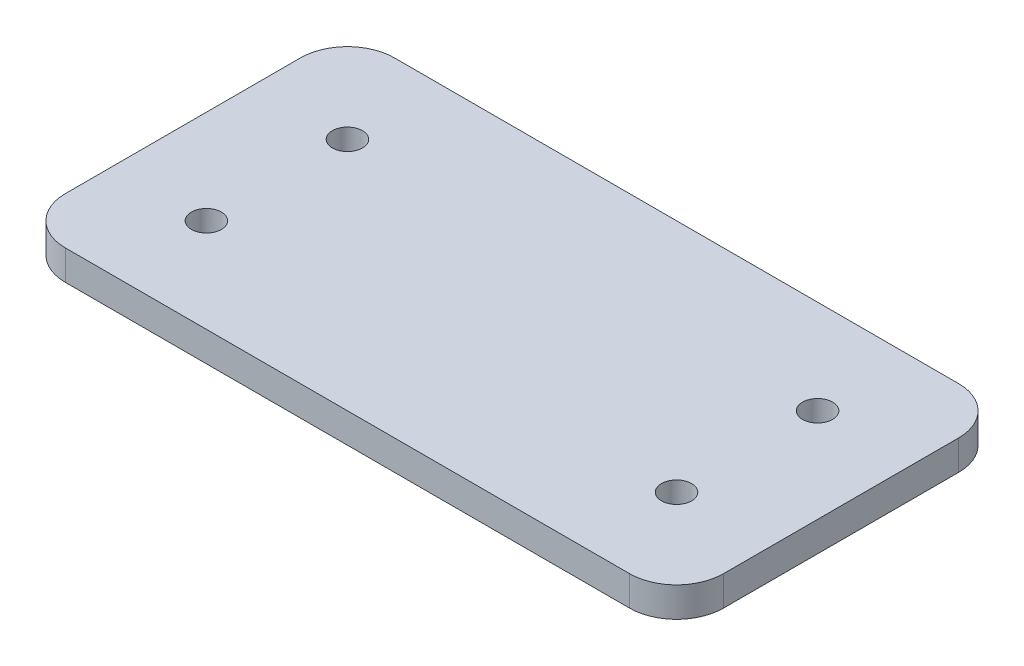
SolidWorks part; units mm, degrees
ref_plane "Front Plane" through (0, 0, 0) normal (0, 0, 1) x (1, 0, 0)
ref_plane "Top Plane" through (0, 0, 0) normal (0, 1, 0) x (1, 0, 0)
ref_plane "Right Plane" through (0, 0, 0) normal (1, 0, 0) x (0, 0, -1)
sketch "Sketch1" plane through (0, 0, 0) normal (0, 1, 0) x (1, 0, 0)
  line L1 (-25, 7.5) -> (25, 7.5) construction
  line L2 (-25, 7.5) -> (-25, -7.5) construction
  line L3 (-25, -7.5) -> (25, -7.5) construction
  line L4 (25, 7.5) -> (25, -7.5) construction
  line L5 (-25, 7.5) -> (25, -7.5) construction
  line L6 (-25, -7.5) -> (25, 7.5) construction
  line L7 (-35, 17.5) -> (35, 17.5)
  line L8 (-35, 17.5) -> (-35, -17.5)
  line L9 (-35, -17.5) -> (35, -17.5)
  line L10 (35, 17.5) -> (35, -17.5)
  line L11 (-35, 17.5) -> (35, -17.5) construction
  line L12 (-35, -17.5) -> (35, 17.5) construction
  point P0 (0, 0)
  point P6 (0, 0)
  dimension "D1" = 15
  dimension "D2" = 50
  dimension "D3" = 10
  dimension "D4" = 10
extrude "Boss-Extrude1" add sketch "Sketch1" along normal blind 3.175
sketch "Sketch2" plane through (0, 3.175, 0) normal (0, 1, 0) x (1, 0, 0)
  line L0 (35, -17.5) -> (35, 17.5) construction
  line L1 (-25, 7.5) -> (25, 7.5) construction
  line L2 (-25, 7.5) -> (-25, -7.5) construction
  line L3 (-25, -7.5) -> (25, -7.5) construction
  line L4 (25, 7.5) -> (25, -7.5) construction
  line L5 (-25, 7.5) -> (25, -7.5) construction
  line L6 (-25, -7.5) -> (25, 7.5) construction
  line L7 (-35, -17.5) -> (35, -17.5) construction
  circle A0 centre (-25, 7.5) radius 1.6
  circle A1 centre (-25, -7.5) radius 1.6
  circle A2 centre (25, -7.5) radius 1.6
  circle A3 centre (25, 7.5) radius 1.6
  point P0 (0, 0)
  dimension "D3" = 3.2
  dimension "D1" = 10
  dimension "D2" = 10
extrude "Cut-Extrude1" cut sketch "Sketch2" against normal blind 3.175
fillet "Fillet1" radius 5 4 edges at (35, 1.5875, 17.5) (35, 1.5875, -17.5) (-35, 1.5875, -17.5) (-35, 1.5875, 17.5)
